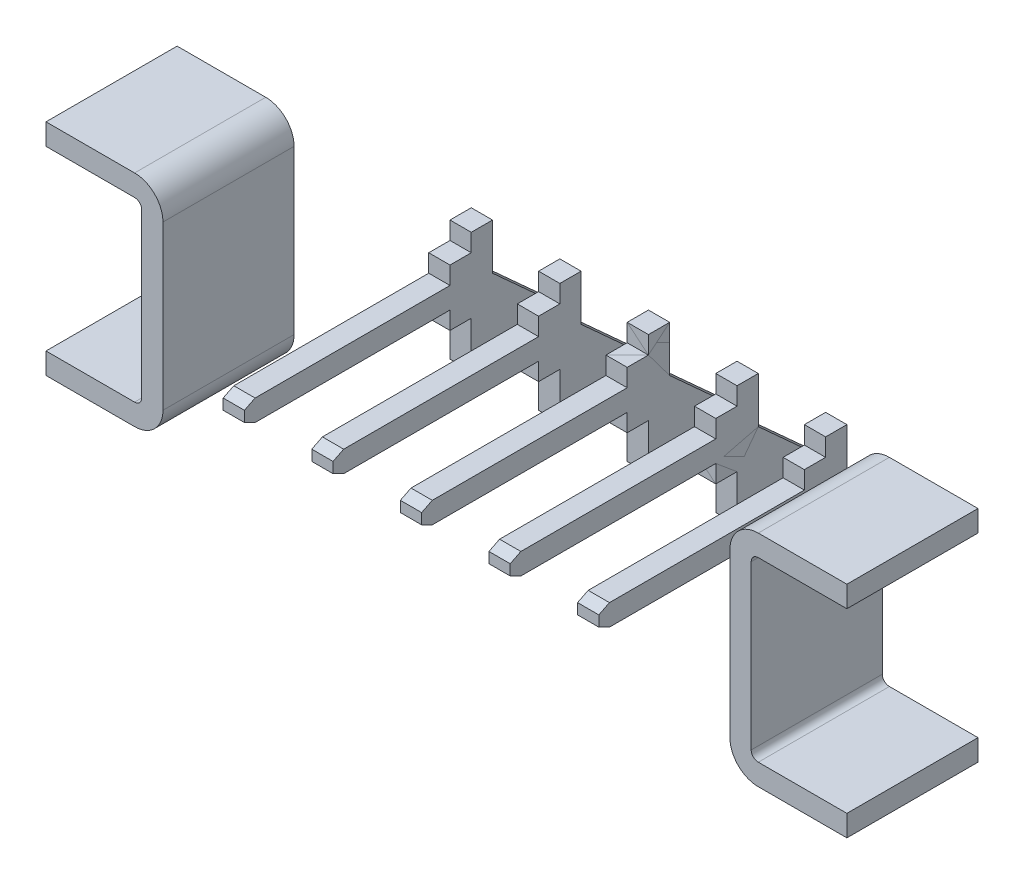
SolidWorks part; units mm, degrees
ref_plane "Front" through (0, 0, 0) normal (0, 0, 1) x (1, 0, 0)
ref_plane "Top" through (0, 0, 0) normal (0, 1, 0) x (1, 0, 0)
ref_plane "Right" through (0, 0, 0) normal (1, 0, 0) x (0, 0, -1)
sketch "Sketch2" plane through (0, 0, 0) normal (1, 0, 0) x (0, 0, -1)
  line L0 (3.8, 1.8) -> (3.8, 1.55)
  line L1 (0, 1.9835) -> (0, 0) construction
  line L2 (3.8, 1.55) -> (1.05, 1.55)
  line L3 (0.9, 1.475) -> (0.9, 1.325)
  line L4 (0, 0) -> (3.8965, 0) construction
  line L5 (1.05, 1.25) -> (3.8, 1.25)
  line L6 (3.8, 1.25) -> (3.8, 1)
  line L7 (3.8, 1) -> (4.1, 1)
  line L9 (4.1, 1) -> (4.1, 0.35)
  line L12 (4.1, 0.35) -> (4.55, 0.35)
  line L13 (4.55, 0.35) -> (4.55, 0)
  line L14 (4.55, 0) -> (5.5, 0)
  line L15 (5.5, 0) -> (5.5, 0.4)
  line L16 (5.5, 0.4) -> (4.4, 1.4)
  line L18 (4.4, 1.4) -> (4.4, 2.05)
  line L19 (4.4, 2.05) -> (4.1, 2.05)
  line L21 (4.1, 2.05) -> (4.1, 1.8)
  line L22 (4.1, 1.8) -> (3.8, 1.8)
  line L23 (0.9, 1.4) -> (4.4, 1.4) construction
  line L24 (0.9, 1.475) -> (1.05, 1.55)
  line L25 (0.9, 1.325) -> (1.05, 1.25)
  point P8 (0.9, 1.4)
  dimension "D1" = 0.3
  dimension "D2" = 0.15
  dimension "D3" = 0.075
  dimension "D4" = 0.25
  dimension "D5" = 0.35
  dimension "D6" = 0.15
  dimension "D7" = 5.5
  dimension "D8" = 0.4
  dimension "D9" = 1.4
  dimension "D10" = 0.8
  dimension "D11" = 0.95
  dimension "D12" = 0.45
  dimension "D13" = 0.6
  dimension "D14" = 0.9
extrude "Boss-Extrude1" add sketch "Sketch2" along normal mid plane 0.3 contours L2 L24 L3 L25 L5 L6 L7 L9 L12 L13 L14 L15 L16 L18 L19 L21 L22 L0
pattern_linear "LPattern1" count 3 spacing 1.25 along (-1, 0, 0) count 3 spacing 1.25 along (1, 0, 0) of bodies 101
sketch "Sketch3" plane through (0, 0, 0) normal (0, 0, 1) x (1, 0, 0)
  line L0 (5.65, 2.95) -> (4.4, 2.95)
  line L1 (4.15, 2.7) -> (4.15, 0.4)
  line L2 (4.4, 0.15) -> (5.65, 0.15)
  line L6 (0, 0) -> (0, 4.4729) construction
  line L9 (-4.4, 0.15) -> (-5.65, 0.15)
  line L10 (-4.15, 2.7) -> (-4.15, 0.4)
  line L11 (-5.65, 2.95) -> (-4.4, 2.95)
  line L12 (0, 0) -> (5.7543, 0) construction
  arc A0 (4.4, 2.95) -> (4.15, 2.7) centre (4.4, 2.7) ccw
  arc A1 (4.15, 0.4) -> (4.4, 0.15) centre (4.4, 0.4) ccw
  arc A2 (-4.15, 0.4) -> (-4.4, 0.15) centre (-4.4, 0.4) cw
  arc A3 (-4.4, 2.95) -> (-4.15, 2.7) centre (-4.4, 2.7) cw
  dimension "D4" = 0.25
  dimension "D3" = 0.15
  dimension "D1" = 2.8
  dimension "D2" = 8.3
  dimension "D5" = 11.3
extrude "Extrude-Thin1" add sketch "Sketch3" against normal blind 1.85 from offset 1.4 separate body thin thin type mid plane wall 0.3 offset against normal yes
